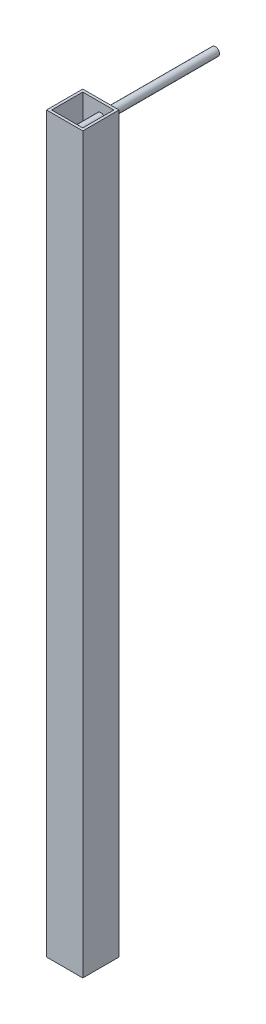
SolidWorks part; units mm, degrees
ref_plane "Front Plane" through (0, 0, 0) normal (0, 0, 1) x (1, 0, 0)
ref_plane "Top Plane" through (0, 0, 0) normal (0, 1, 0) x (1, 0, 0)
ref_plane "Right Plane" through (0, 0, 0) normal (1, 0, 0) x (0, 0, -1)
sketch "Sketch1" plane through (0, 0, 0) normal (0, 1, 0) x (1, 0, 0)
  line L0 (-17.5, -17.5) -> (17.5, -17.5)
  line L1 (-15, 15) -> (15, 15)
  line L2 (-15, 15) -> (-15, -15)
  line L3 (-15, -15) -> (15, -15)
  line L4 (15, 15) -> (15, -15)
  line L5 (-15, 15) -> (15, -15) construction
  line L6 (-15, -15) -> (15, 15) construction
  line L7 (17.5, 17.5) -> (17.5, -17.5)
  line L8 (-17.5, 17.5) -> (17.5, 17.5)
  line L9 (-17.5, 17.5) -> (-17.5, -17.5)
  point P0 (0, 0)
  dimension "D1" = 2.5
extrude "Boss-Extrude1" add sketch "Sketch1" along normal blind 708
sketch "Sketch2" plane through (0, 0, 15) normal (0, 0, -1) x (-1, 0, 0)
  circle A1 centre (-2.4686, 695.4772) radius 4
  circle A2 centre (-2.4686, 695.4772) radius 4
  dimension "D1" = 0
extrude "Boss-Extrude2" add sketch "Sketch2" along normal blind 140.5
